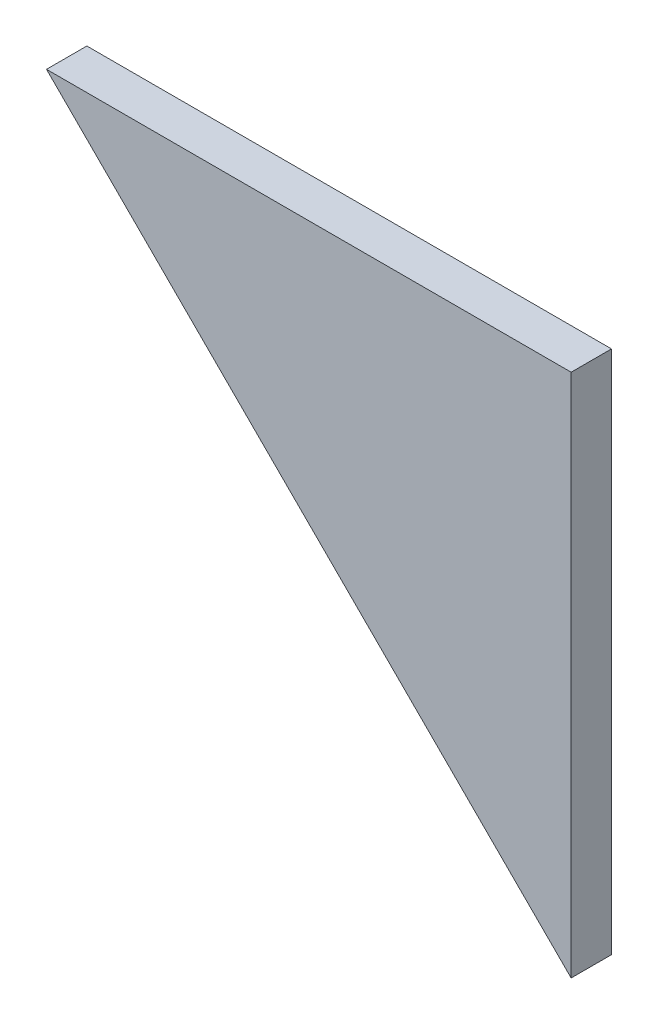
SolidWorks part; units mm, degrees
ref_plane "Front Plane" through (0, 0, 0) normal (0, 0, 1) x (1, 0, 0)
ref_plane "Top Plane" through (0, 0, 0) normal (0, 1, 0) x (1, 0, 0)
ref_plane "Right Plane" through (0, 0, 0) normal (1, 0, 0) x (0, 0, -1)
sketch "Sketch1" plane through (0, 0, 0) normal (0, 0, 1) x (1, 0, 0)
  line L0 (965, -169.5) -> (939, -143.5)
  line L2 (939, -143.5) -> (965, -143.5)
  line L3 (965, -143.5) -> (965, -169.5)
  dimension "D1" = 26
extrude "Boss-Extrude1" add sketch "Sketch1" against normal blind 2
